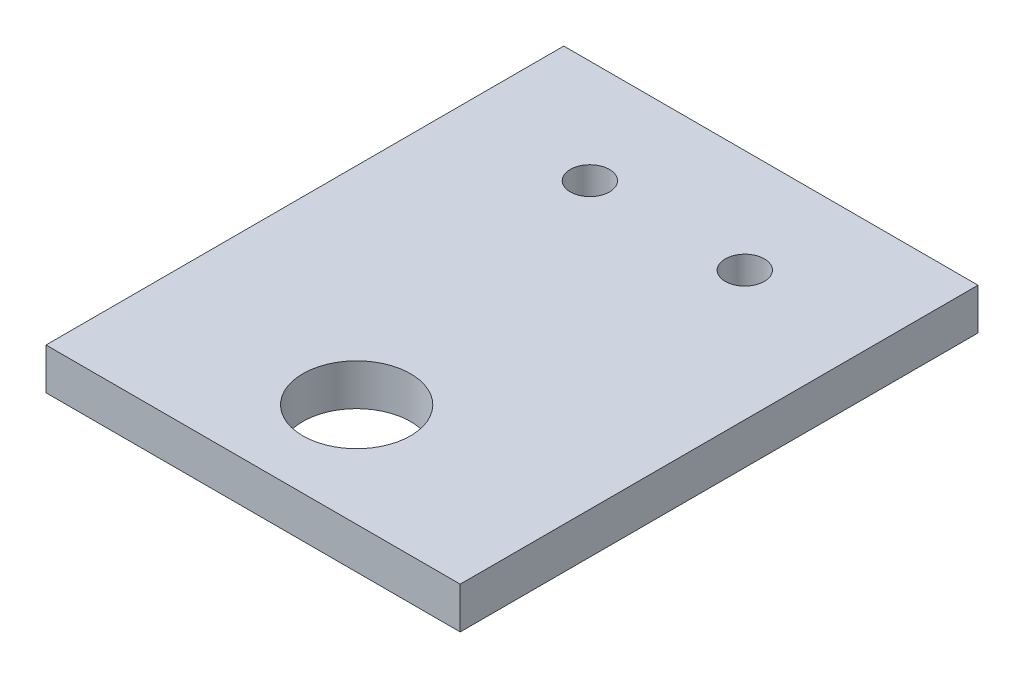
SolidWorks part; units mm, degrees
ref_plane "Front Plane" through (0, 0, 0) normal (0, 0, 1) x (1, 0, 0)
ref_plane "Top Plane" through (0, 0, 0) normal (0, 1, 0) x (1, 0, 0)
ref_plane "Right Plane" through (0, 0, 0) normal (1, 0, 0) x (0, 0, -1)
sketch "Sketch2" plane through (0, 0, 0) normal (0, 1, 0) x (1, 0, 0)
  line L1 (-6.8943, 7.1664) -> (18.5057, 7.1664)
  line L2 (-6.8943, 7.1664) -> (-6.8943, -24.5836)
  line L3 (-6.8943, -24.5836) -> (18.5057, -24.5836)
  line L4 (18.5057, 7.1664) -> (18.5057, -24.5836)
  dimension "D1" = 25.4
  dimension "D2" = 31.75
extrude "Boss-Extrude1" add sketch "Sketch2" along normal blind 2.54
hole_wizard "Ø2.4 (2.4) Diameter Slot2" positions "Sketch7" profile "Sketch6" size "Ø2.4" standard "ANSI Metric" slot yes end condition through all
sketch "Sketch7" plane through (0, 2.54, 0) normal (0, 1, 0) x (1, 0, 0)
  line L0 (1.0557, 0.8164) -> (-6.8943, 0.8164)
  line L1 (-6.8943, 7.1664) -> (-6.8943, -24.5836) construction
  line L3 (10.5557, 0.8164) -> (18.5057, 0.8164)
  line L4 (18.5057, -24.5836) -> (18.5057, 7.1664) construction
  line L5 (18.5057, 7.1664) -> (-6.8943, 7.1664) construction
  point P0 (1.0557, 0.8164)
  point P2 (10.5557, 0.8164)
  dimension "D1" = 9.5
  dimension "D2" = 6.35
sketch "Sketch6" plane through (1.0557, 2.54, -0.8164) normal (1, 0, 0) x (0, 0, 1)
  line L0 (0, 0) -> (0, 2.54)
  line L1 (0, 2.54) -> (1.2, 2.54)
  line L2 (1.2, 2.54) -> (1.2, 0)
  line L5 (1.2, 0) -> (0, 0)
  line L11 (0, -6.35) -> (0, 107.95) construction
  dimension "Thru Hole Dia." = 2.4
  dimension "Thru Hole Depth" = 2.54
sketch "Sketch10" plane through (0, 2.54, 0) normal (0, 1, 0) x (1, 0, 0)
  line L0 (5.8057, -18.2336) -> (5.8057, -24.5836)
  line L1 (-6.8943, -24.5836) -> (18.5057, -24.5836) construction
  circle A0 centre (5.8057, -18.2336) radius 3.302
  dimension "D1" = 6.35
  dimension "D2" = 6.604
extrude "Cut-Extrude1" cut sketch "Sketch10" against normal blind 3.175
